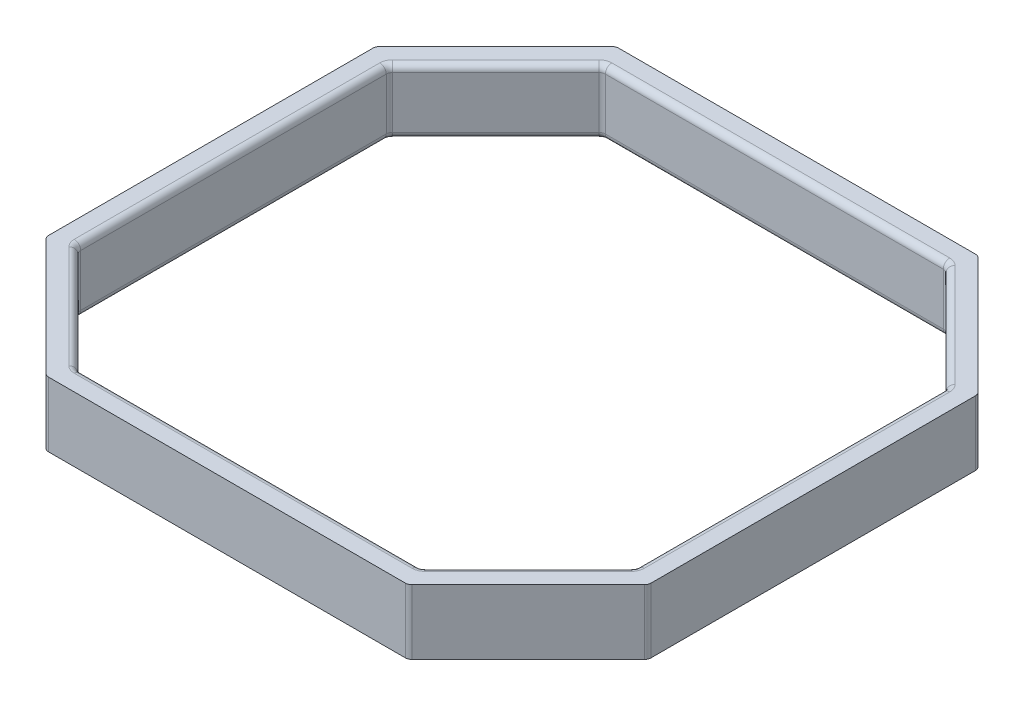
SolidWorks part; units mm, degrees
material "CopperWire"
ref_plane "Front Plane" through (0, 0, 0) normal (0, 0, 1) x (1, 0, 0)
ref_plane "Top Plane" through (0, 0, 0) normal (0, 1, 0) x (1, 0, 0)
ref_plane "Right Plane" through (0, 0, 0) normal (1, 0, 0) x (0, 0, -1)
sketch "Sketch1" plane through (0, 0, 0) normal (0, 1, 0) x (1, 0, 0)
  line L0 (-43, 24) -> (-26.5, 40.5)
  line L1 (-26.5, -40.5) -> (26.5, -40.5)
  line L2 (-43, -24) -> (-43, 24)
  line L3 (-26.5, 40.5) -> (26.5, 40.5)
  line L4 (43, -24) -> (43, 24)
  line L5 (0, 0) -> (0, -40.5) construction
  line L6 (0, 0) -> (-43, 0) construction
  line L7 (-43, -24) -> (-26.5, -40.5)
  line L8 (26.5, -40.5) -> (43, -24)
  line L9 (26.5, 40.5) -> (43, 24)
  line L10 (0, 0) -> (0, 40.5) construction
  line L11 (0, 0) -> (43, 0) construction
  line L12 (-46.5, 25.4497) -> (-27.9497, 44)
  line L13 (-27.9497, 44) -> (27.9497, 44)
  line L14 (27.9497, 44) -> (46.5, 25.4497)
  line L15 (46.5, -25.4497) -> (46.5, 25.4497)
  line L16 (27.9497, -44) -> (46.5, -25.4497)
  line L17 (-27.9497, -44) -> (27.9497, -44)
  line L18 (-46.5, -25.4497) -> (-27.9497, -44)
  line L19 (-46.5, -25.4497) -> (-46.5, 25.4497)
  point P0 (0, 0)
  dimension "D1" = 86
  dimension "D2" = 81
  dimension "D3" = 48
  dimension "D4" = 53
  dimension "D5" = 3.5
extrude "Boss-Extrude1" add sketch "Sketch1" along normal blind 10
fillet "Fillet1" radius 1 32 edges at (-43, 10, 0) (-43, 0, 0) (0, 10, -40.5) (0, 0, -40.5) (43, 10, 0) (43, 0, 0) (0, 10, 40.5) (0, 0, 40.5) (-26.5, 5, 40.5) (-34.75, 10, 32.25) (-43, 5, 24) (-34.75, 0, 32.25) (-43, 5, -24) (-34.75, 10, -32.25) (-26.5, 5, -40.5) (-34.75, 0, -32.25) (26.5, 5, -40.5) (34.75, 10, -32.25) (43, 5, -24) (34.75, 0, -32.25) (43, 5, 24) (34.75, 10, 32.25) (26.5, 5, 40.5) (34.75, 0, 32.25) (-46.5, 5, -25.4497) (-27.9497, 5, -44) (-46.5, 5, 25.4497) (-27.9497, 5, 44) (27.9497, 5, 44) (46.5, 5, 25.4497) (46.5, 5, -25.4497) (27.9497, 5, -44)
